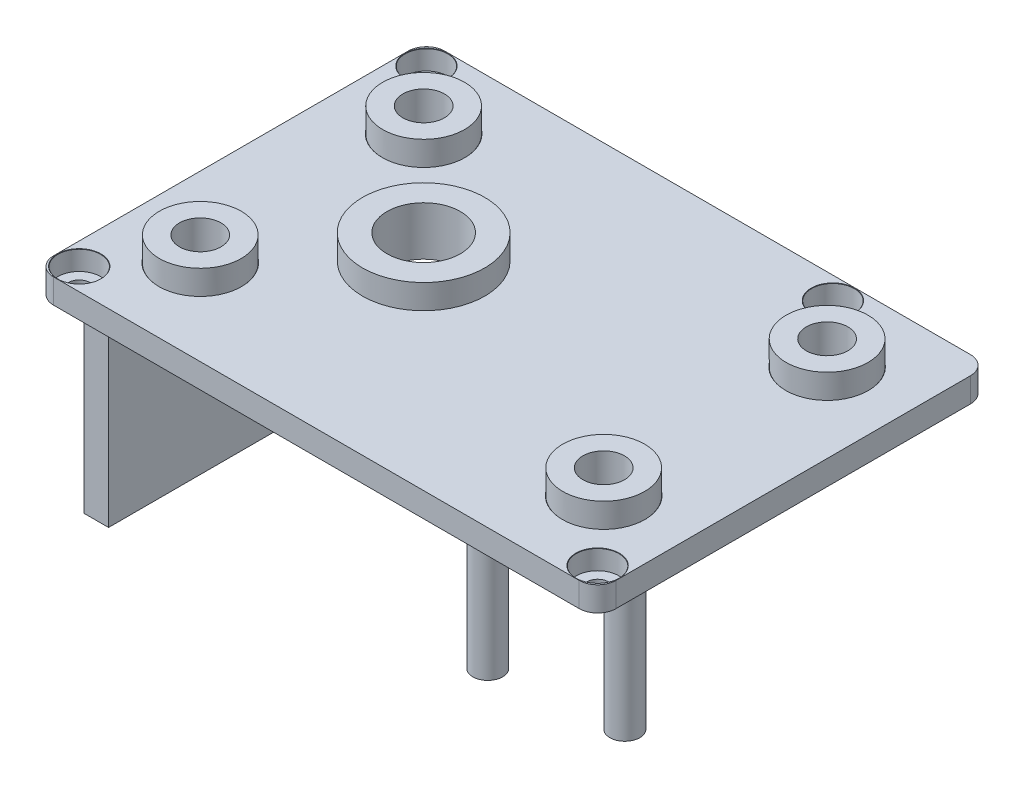
SolidWorks part; units mm, degrees
material "AISI 1020"
ref_plane "Front Plane" through (0, 0, 0) normal (0, 0, 1) x (1, 0, 0)
ref_plane "Top Plane" through (0, 0, 0) normal (0, 1, 0) x (1, 0, 0)
ref_plane "Right Plane" through (0, 0, 0) normal (1, 0, 0) x (0, 0, -1)
sketch "Sketch1" plane through (0, 0, 0) normal (0, 1, 0) x (1, 0, 0)
  line L1 (0, 0) -> (-46, 0)
  line L2 (0, 0) -> (0, -32)
  line L3 (0, -32) -> (-46, -32)
  line L4 (-46, 0) -> (-46, -32)
  dimension "D1" = 32
  dimension "D2" = 46
extrude "Boss-Extrude1" add sketch "Sketch1" along normal blind 2 contours L2 L1 L4 L3
sketch "Sketch3" plane through (-49.8871, 2, -0.2737) normal (0, 1, 0) x (1, 0, 0)
  line L2 (49.8871, -0.2737) -> (3.8871, -0.2737) construction
  line L3 (3.8871, -0.2737) -> (3.8871, -32.2737) construction
  point P0 (10.3871, -7.2737)
  point P1 (10.3871, -25.3886)
  point P2 (43.3871, -25.3886)
  point P3 (43.3871, -7.2737)
  dimension "D1" = 7
  dimension "D2" = 6.5
  dimension "D3" = 33
hole_wizard "CBORE for M3 SBHCS1" positions "Sketch5" profile "Sketch7" counterbore size "M3" standard "ANSI Metric"
sketch "Sketch5" plane through (-49.8871, 2, -0.2737) normal (0, 1, 0) x (1, 0, 0)
  line L0 (3.8871, -0.2737) -> (3.8871, -32.2737) construction
  line L2 (49.8871, -32.2737) -> (3.8871, -32.2737) construction
  point P0 (10.3871, -7)
  point P3 (10.3871, -25.2737)
  point P6 (43.3871, -25.2737)
  point P9 (43.3871, -7)
  dimension "D1" = 6.5
  dimension "D2" = 6.5
  dimension "D3" = 33
  dimension "D4" = 33
  dimension "D5" = 7
  dimension "D6" = 7
sketch "Sketch7" plane through (-39.5, 2, 6.7263) normal (1, 0, 0) x (0, 0, 1)
  line L0 (0, 0) -> (0, 3.0215)
  line L1 (0, 3.0215) -> (1.7, 2)
  line L2 (1.7, 2) -> (1.7, 1.65)
  line L3 (1.7, 1.65) -> (3.35, 1.65)
  line L5 (3.35, 1.65) -> (3.35, 0.025)
  line L6 (3.35, 0.025) -> (3.375, 0)
  line L7 (3.375, 0) -> (0, 0)
  line L8 (-3.35, 0.025) -> (-3.375, 0) construction
  line L10 (0, 3.0215) -> (-1.7, 2) construction
  line L11 (0, -6.35) -> (0, 107.95) construction
  dimension "Hole Dia." = 3.4
  dimension "Hole Depth" = 2
  dimension "C'Bore Dia." = 6.7
  dimension "C'Bore Depth" = 1.65
  dimension "Near C'Sink Dia." = 6.75
  dimension "Near C'Sink Angle" = 90
  dimension "Drill Angle" = 118
sketch "Sketch9" plane through (-49.8871, 0.35, -0.2737) normal (0, 1, 0) x (1, 0, 0)
  line L0 (49.8871, -0.2737) -> (3.8871, -0.2737) construction
  circle A0 centre (10.3871, -25.2737) radius 3.35 construction
  circle A1 centre (43.3871, -25.2737) radius 3.35 construction
  circle A2 centre (43.3871, -7) radius 3.35 construction
  circle A3 centre (10.3871, -7) radius 3.35 construction
  circle A4 centre (10.3871, -25.2737) radius 3.35
  circle A5 centre (43.3871, -25.2737) radius 3.35
  circle A6 centre (43.3871, -7) radius 3.35
  circle A7 centre (10.3871, -7) radius 3.35
  circle A8 centre (10.3871, -25.2737) radius 1.7 construction
  circle A9 centre (43.3871, -25.2737) radius 1.7 construction
  circle A10 centre (43.3871, -7) radius 1.7 construction
  circle A11 centre (10.3871, -7) radius 1.7 construction
  circle A12 centre (10.3871, -25.2737) radius 1.7
  circle A13 centre (43.3871, -25.2737) radius 1.7
  circle A14 centre (43.3871, -7) radius 1.7
  circle A15 centre (10.3871, -7) radius 1.7
  dimension "D1" = 6.7263
extrude "Boss-Extrude2" add sketch "Sketch9" along normal blind 3.63
sketch "Sketch11" plane through (-49.8871, 2, -0.2737) normal (0, 1, 0) x (1, 0, 0)
  line L0 (3.8871, -0.2737) -> (3.8871, -32.2737) construction
  circle A0 centre (19.3871, -16) radius 5
  circle A1 centre (19.3871, -16) radius 3
  dimension "D1" = 10
  dimension "D2" = 15.5
extrude "Boss-Extrude3" add sketch "Sketch11" along normal blind 2
sketch "Sketch12" plane through (-49.8871, 2, -0.2737) normal (0, 1, 0) x (1, 0, 0)
  point P0 (1.8, -1.8)
  point P1 (35.05, -1.8)
  point P2 (1.8, -30.2)
  point P3 (44.2, -30.2)
hole_wizard "CBORE for M1.6 SHCS1" positions "Sketch14" profile "Sketch16" counterbore size "M1.6" standard "ANSI Metric" end condition through all
sketch "Sketch14" plane through (-49.8871, 2, -0.2737) normal (0, 1, 0) x (1, 0, 0)
  line L1 (3.8871, -0.2737) -> (3.8871, -32.2737) construction
  line L2 (49.8871, -0.2737) -> (3.8871, -0.2737) construction
  line L3 (49.8871, -0.2737) -> (49.8871, -32.2737) construction
  line L4 (49.8871, -32.2737) -> (3.8871, -32.2737) construction
  circle A0 centre (43.3871, -7) radius 1.7 construction
  point P0 (5.6871, -2.0737)
  point P3 (38.9371, -2.0737)
  point P6 (48.0871, -30.4737)
  point P9 (5.6871, -30.4737)
  dimension "D1" = 1.8
  dimension "D2" = 1.8
  dimension "D3" = 4.45
  dimension "D4" = 1.8
  dimension "D5" = 1.8
sketch "Sketch16" plane through (-44.2, 2, 1.8) normal (1, 0, 0) x (0, 0, 1)
  line L0 (0, 0) -> (0, 2)
  line L1 (0, 2) -> (0.9, 2)
  line L3 (0.9, 2) -> (0.9, 1.6)
  line L4 (1.75, 1.6) -> (0.9, 1.6)
  line L5 (1.75, 1.6) -> (1.75, 0.025)
  line L6 (1.75, 0.025) -> (1.775, 0)
  line L7 (1.775, 0) -> (0, 0)
  line L8 (-1.75, 0.025) -> (-1.775, 0) construction
  line L11 (0, -6.35) -> (0, 107.95) construction
  dimension "Thru Hole Dia." = 1.8
  dimension "Thru Hole Depth" = 2
  dimension "C'Bore Dia." = 3.5
  dimension "C'Bore Depth" = 1.6
  dimension "Near C'Sink Dia." = 3.55
  dimension "Near C'Sink Angle" = 90
sketch "Sketch17" plane through (0, 2, 0) normal (0, 1, 0) x (1, 0, 0)
  circle A1 centre (-30.5, -15.7263) radius 3
  circle A2 centre (-30.5, -15.7263) radius 3
  dimension "D1" = 0
extrude "Cut-Extrude1" cut sketch "Sketch17" along direction (0, 1, 0) on the side against the normal up to surface (2 mm away)
fillet "Fillet1" radius 1.5 4 edges at (0, 1, 0) (0, 1, 32) (-46, 1, 32) (-46, 1, 0)
sketch "Sketch18" plane through (0, 0, 0) normal (0, -1, 0) x (1, 0, 0)
  line L0 (-46, 1.5) -> (-46, 30.5) construction
  line L1 (-46, 28) -> (-44, 28)
  line L2 (-46, 28) -> (-46, 4)
  line L3 (-46, 4) -> (-44, 4)
  line L4 (-44, 28) -> (-44, 4)
  line L5 (-1.5, 32) -> (-44.5, 32) construction
  line L6 (-1.5, 0) -> (-44.5, 0) construction
  dimension "D1" = 4
  dimension "D2" = 4
  dimension "D3" = 2
extrude "Boss-Extrude4" add sketch "Sketch18" along normal blind 17.5
sketch "Sketch19" plane through (0, 0, 0) normal (0, -1, 0) x (1, 0, 0)
  circle A0 centre (-18.5161, 22.4677) radius 1.215
  circle A1 centre (-8.6009, 21.1677) radius 1.22
extrude "Boss-Extrude5" add sketch "Sketch19" along normal up to surface (17.5 mm away)
